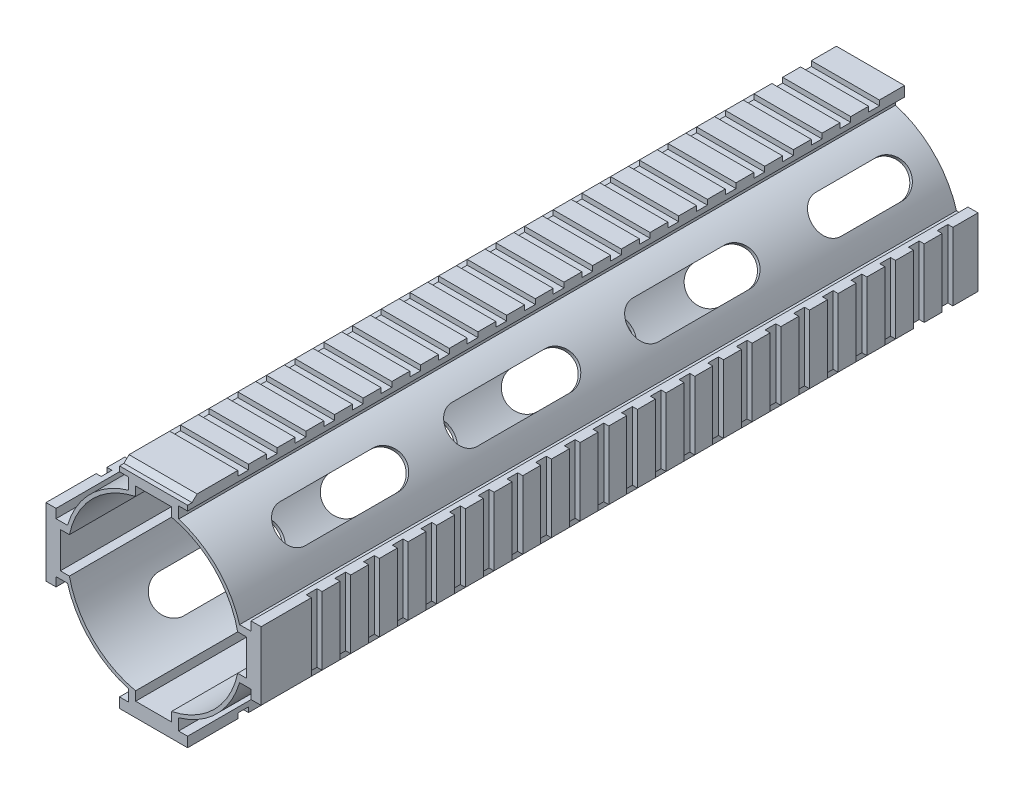
SolidWorks part; units mm, degrees
ref_plane "前视基准面" through (0, 0, 0) normal (0, 0, 1) x (1, 0, 0)
ref_plane "上视基准面" through (0, 0, 0) normal (0, 1, 0) x (1, 0, 0)
ref_plane "右视基准面" through (0, 0, 0) normal (1, 0, 0) x (0, 0, -1)
other "Configuration Table"
sketch "草图1" plane through (0, 0, 0) normal (0, 0, 1) x (1, 0, 0)
  line L1 (5, -23.4734) -> (5, -26)
  line L2 (5, -26) -> (-5, -26)
  line L3 (-5, -26) -> (-5, -23.4734)
  line L4 (0, 0) -> (0, -26) construction
  line L5 (-26, 5) -> (-23.4734, 5)
  line L6 (-26, -5) -> (-26, 5)
  line L7 (-23.4734, -5) -> (-26, -5)
  line L8 (5, 26) -> (5, 23.4734)
  line L9 (-5, 26) -> (5, 26)
  line L10 (-5, 23.4734) -> (-5, 26)
  line L11 (26, -5) -> (23.4734, -5)
  line L12 (26, 5) -> (26, -5)
  line L13 (23.4734, 5) -> (26, 5)
  arc A0 (5, -23.4734) -> (23.4734, -5) centre (0, 0) ccw
  arc A1 (-23.4734, -5) -> (-5, -23.4734) centre (0, 0) ccw
  arc A2 (-5, 23.4734) -> (-23.4734, 5) centre (0, 0) ccw
  arc A3 (23.4734, 5) -> (5, 23.4734) centre (0, 0) ccw
  point P22 (0, 0)
  dimension "D1" = 48
  dimension "D3" = 10
  dimension "D4" = 52
  dimension "D2" = 4
sketch "草图2" plane through (0, 0, 0) normal (0, 0, 1) x (1, 0, 0)
  line L1 (7, -24) -> (7, -27.2)
  line L3 (-7, -27.2) -> (-7, -24)
  line L4 (0, 0) -> (0, -28.1529) construction
  line L5 (-7, -27.2) -> (-9.5, -27.2)
  line L6 (-9.5, -27.2) -> (-9.5, -30)
  line L7 (-9.5, -30) -> (9.5, -30)
  line L8 (9.5, -30) -> (9.5, -27.2)
  line L9 (9.5, -27.2) -> (7, -27.2)
  line L10 (-24, -7) -> (-27.2, -7)
  line L11 (-27.2, 7) -> (-24, 7)
  line L12 (-27.2, 7) -> (-27.2, 9.5)
  line L13 (-27.2, 9.5) -> (-30, 9.5)
  line L14 (-30, 9.5) -> (-30, -9.5)
  line L15 (-30, -9.5) -> (-27.2, -9.5)
  line L16 (-27.2, -9.5) -> (-27.2, -7)
  line L17 (-5, 23.4734) -> (-5, 26) construction
  line L18 (-7, 24) -> (-7, 27.2)
  line L19 (7, 27.2) -> (7, 24)
  line L20 (7, 27.2) -> (9.5, 27.2)
  line L21 (9.5, 27.2) -> (9.5, 30)
  line L22 (9.5, 30) -> (-9.5, 30)
  line L23 (-9.5, 30) -> (-9.5, 27.2)
  line L24 (-9.5, 27.2) -> (-7, 27.2)
  line L25 (-5, 26) -> (5, 26) construction
  line L26 (24, 7) -> (27.2, 7)
  line L27 (27.2, -7) -> (24, -7)
  line L28 (27.2, -7) -> (27.2, -9.5)
  line L29 (27.2, -9.5) -> (30, -9.5)
  line L30 (30, -9.5) -> (30, 9.5)
  line L31 (30, 9.5) -> (27.2, 9.5)
  line L32 (27.2, 9.5) -> (27.2, 7)
  line L33 (5, 26) -> (5, 23.4734) construction
  line L34 (-25, 0) -> (-28.1529, 0) construction
  line L35 (0, 0) -> (0, 25) construction
  line L36 (25, 0) -> (28.1529, 0) construction
  line L37 (23.4734, 5) -> (26, 5) construction
  line L38 (26, 5) -> (26, -5) construction
  line L39 (26, -5) -> (23.4734, -5) construction
  line L40 (5, -23.4734) -> (5, -26) construction
  line L41 (5, -26) -> (-5, -26) construction
  line L42 (-5, -26) -> (-5, -23.4734) construction
  line L43 (-26, 5) -> (-23.4734, 5) construction
  line L44 (-23.4734, -5) -> (-26, -5) construction
  line L45 (-26, -5) -> (-26, 5) construction
  line L46 (-5, 23.4734) -> (-5, 26)
  line L47 (-5, 26) -> (5, 26)
  line L48 (5, 26) -> (5, 23.4734)
  line L49 (23.4734, 5) -> (26, 5)
  line L50 (26, 5) -> (26, -5)
  line L51 (26, -5) -> (23.4734, -5)
  line L52 (5, -23.4734) -> (5, -26)
  line L53 (5, -26) -> (-5, -26)
  line L54 (-5, -26) -> (-5, -23.4734)
  line L55 (-26, 5) -> (-23.4734, 5)
  line L56 (-23.4734, -5) -> (-26, -5)
  line L57 (-26, -5) -> (-26, 5)
  arc A0 (7, -24) -> (24, -7) centre (0, 0) ccw
  arc A1 (-24, -7) -> (-7, -24) centre (0, 0) ccw
  arc A2 (-7, 24) -> (-24, 7) centre (0, 0) ccw
  arc A3 (24, 7) -> (7, 24) centre (0, 0) ccw
  arc A4 (23.4734, 5) -> (5, 23.4734) centre (0, 0) ccw construction
  arc A5 (5, -23.4734) -> (23.4734, -5) centre (0, 0) ccw construction
  arc A6 (-23.4734, -5) -> (-5, -23.4734) centre (0, 0) ccw construction
  arc A7 (-5, 23.4734) -> (-23.4734, 5) centre (0, 0) ccw construction
  arc A8 (23.4734, 5) -> (5, 23.4734) centre (0, 0) ccw
  arc A9 (5, -23.4734) -> (23.4734, -5) centre (0, 0) ccw
  arc A10 (-23.4734, -5) -> (-5, -23.4734) centre (0, 0) ccw
  arc A11 (-5, 23.4734) -> (-23.4734, 5) centre (0, 0) ccw
  point P1 (0, -30)
  point P12 (7.5864, -29.0733)
  point P42 (0, 0)
  dimension "D1" = 50
  dimension "D3" = 14
  dimension "D4" = 19
  dimension "D5" = 60
  dimension "D6" = 2.8
  dimension "D7" = 2.8
  dimension "D2" = 4
extrude "凸台-拉伸2" add sketch "草图2" against normal blind 200
ref_plane "基准面2" through (14.2367, 14.2367, 0) normal (0.7071, 0.7071, 0) x (0.7071, -0.7071, 0)
sketch "草图5" plane through (14.2367, 14.2367, 0) normal (0.7071, 0.7071, 0) x (0.7071, -0.7071, 0)
  line L0 (0, 200) -> (0, 0) construction
  line L1 (12.0208, 200) -> (-12.0208, 200) construction
  line L2 (0, 188) -> (0, 171) construction
  line L3 (5, 188) -> (5, 171)
  line L4 (-5, 188) -> (-5, 171)
  line L5 (0, 145.5) -> (0, 120) construction
  line L6 (5, 145.5) -> (5, 120)
  line L7 (-5, 145.5) -> (-5, 120)
  line L8 (0, 95.5) -> (0, 69.5) construction
  line L9 (5, 95.5) -> (5, 69.5)
  line L10 (-5, 95.5) -> (-5, 69.5)
  line L11 (0, 47.5) -> (0, 21.5) construction
  line L12 (5, 47.5) -> (5, 21.5)
  line L13 (-5, 47.5) -> (-5, 21.5)
  arc A0 (5, 188) -> (-5, 188) centre (0, 188) ccw
  arc A1 (-5, 171) -> (5, 171) centre (0, 171) ccw
  arc A2 (5, 145.5) -> (-5, 145.5) centre (0, 145.5) ccw
  arc A3 (-5, 120) -> (5, 120) centre (0, 120) ccw
  arc A4 (5, 95.5) -> (-5, 95.5) centre (0, 95.5) ccw
  arc A5 (-5, 69.5) -> (5, 69.5) centre (0, 69.5) ccw
  arc A6 (5, 47.5) -> (-5, 47.5) centre (0, 47.5) ccw
  arc A7 (-5, 21.5) -> (5, 21.5) centre (0, 21.5) ccw
  point P7 (0, 179.5)
  point P12 (0, 132.75)
  point P19 (0, 82.5)
  point P26 (0, 34.5)
  point P33 (0, 0)
  point P35 (6.6279, 196.4967)
  dimension "D9" = 5
  dimension "D1" = 21.5
  dimension "D2" = 26
  dimension "D3" = 22
  dimension "D4" = 26
  dimension "D5" = 24.5
  dimension "D6" = 25.5
  dimension "D7" = 17
  dimension "D8" = 12
extrude "切除-拉伸2" cut sketch "草图5" along normal through all
sketch "草图6" plane through (0, 0, 0) normal (1, 0, 0) x (0, 0, -1)
  line L0 (200, 30) -> (0, 30) construction
  line L1 (190, 30) -> (193, 30)
  line L2 (190, 30) -> (190, 28.6)
  line L3 (190, 28.6) -> (193, 28.6)
  line L4 (193, 30) -> (193, 28.6)
  line L5 (200, 27.2) -> (200, 30) construction
  line L6 (185, 30) -> (185, 28.6)
  line L7 (182, 30) -> (185, 30)
  line L8 (182, 30) -> (182, 28.6)
  line L9 (182, 28.6) -> (185, 28.6)
  line L10 (177, 30) -> (177, 28.6)
  line L11 (174, 30) -> (177, 30)
  line L12 (174, 30) -> (174, 28.6)
  line L13 (174, 28.6) -> (177, 28.6)
  line L14 (169, 30) -> (169, 28.6)
  line L15 (166, 30) -> (169, 30)
  line L16 (166, 30) -> (166, 28.6)
  line L17 (166, 28.6) -> (169, 28.6)
  line L18 (161, 30) -> (161, 28.6)
  line L19 (158, 30) -> (161, 30)
  line L20 (158, 30) -> (158, 28.6)
  line L21 (158, 28.6) -> (161, 28.6)
  line L22 (153, 30) -> (153, 28.6)
  line L23 (150, 30) -> (153, 30)
  line L24 (150, 30) -> (150, 28.6)
  line L25 (150, 28.6) -> (153, 28.6)
  line L26 (145, 30) -> (145, 28.6)
  line L27 (142, 30) -> (145, 30)
  line L28 (142, 30) -> (142, 28.6)
  line L29 (142, 28.6) -> (145, 28.6)
  line L30 (137, 30) -> (137, 28.6)
  line L31 (134, 30) -> (137, 30)
  line L32 (134, 30) -> (134, 28.6)
  line L33 (134, 28.6) -> (137, 28.6)
  line L34 (129, 30) -> (129, 28.6)
  line L35 (126, 30) -> (129, 30)
  line L36 (126, 30) -> (126, 28.6)
  line L37 (126, 28.6) -> (129, 28.6)
  line L38 (121, 30) -> (121, 28.6)
  line L39 (118, 30) -> (121, 30)
  line L40 (118, 30) -> (118, 28.6)
  line L41 (118, 28.6) -> (121, 28.6)
  line L42 (113, 30) -> (113, 28.6)
  line L43 (110, 30) -> (113, 30)
  line L44 (110, 30) -> (110, 28.6)
  line L45 (110, 28.6) -> (113, 28.6)
  line L46 (105, 30) -> (105, 28.6)
  line L47 (102, 30) -> (105, 30)
  line L48 (102, 30) -> (102, 28.6)
  line L49 (102, 28.6) -> (105, 28.6)
  line L50 (97, 30) -> (97, 28.6)
  line L51 (94, 30) -> (97, 30)
  line L52 (94, 30) -> (94, 28.6)
  line L53 (94, 28.6) -> (97, 28.6)
  line L54 (89, 30) -> (89, 28.6)
  line L55 (86, 30) -> (89, 30)
  line L56 (86, 30) -> (86, 28.6)
  line L57 (86, 28.6) -> (89, 28.6)
  line L58 (81, 30) -> (81, 28.6)
  line L59 (78, 30) -> (81, 30)
  line L60 (78, 30) -> (78, 28.6)
  line L61 (78, 28.6) -> (81, 28.6)
  line L62 (73, 30) -> (73, 28.6)
  line L63 (70, 30) -> (73, 30)
  line L64 (70, 30) -> (70, 28.6)
  line L65 (70, 28.6) -> (73, 28.6)
  line L66 (65, 30) -> (65, 28.6)
  line L67 (62, 30) -> (65, 30)
  line L68 (62, 30) -> (62, 28.6)
  line L69 (62, 28.6) -> (65, 28.6)
  line L70 (57, 30) -> (57, 28.6)
  line L71 (54, 30) -> (57, 30)
  line L72 (54, 30) -> (54, 28.6)
  line L73 (54, 28.6) -> (57, 28.6)
  line L74 (49, 30) -> (49, 28.6)
  line L75 (46, 30) -> (49, 30)
  line L76 (46, 30) -> (46, 28.6)
  line L77 (46, 28.6) -> (49, 28.6)
  line L78 (41, 30) -> (41, 28.6)
  line L79 (38, 30) -> (41, 30)
  line L80 (38, 30) -> (38, 28.6)
  line L81 (38, 28.6) -> (41, 28.6)
  line L82 (33, 30) -> (33, 28.6)
  line L83 (30, 30) -> (33, 30)
  line L84 (30, 30) -> (30, 28.6)
  line L85 (30, 28.6) -> (33, 28.6)
  line L86 (25, 30) -> (25, 28.6)
  line L87 (22, 30) -> (25, 30)
  line L88 (22, 30) -> (22, 28.6)
  line L89 (22, 28.6) -> (25, 28.6)
  line L90 (17, 30) -> (17, 28.6)
  line L91 (14, 30) -> (17, 30)
  line L92 (14, 30) -> (14, 28.6)
  line L93 (14, 28.6) -> (17, 28.6)
  dimension "D1" = 3
  dimension "D2" = 7
  dimension "D3" = 1.4
  dimension "D5" = 8
  dimension "D4" = 23
extrude "切除-拉伸3" cut sketch "草图6" against normal mid plane 200
sketch "草图7" plane through (0, 0, 0) normal (1, 0, 0) x (0, 0, -1)
  line L0 (0, 28.6) -> (1.25, 28.6)
  line L1 (0, 27.2) -> (0, 30) construction
  line L2 (1.25, 28.6) -> (2.65, 30)
  line L3 (14, 30) -> (0, 30) construction
  line L4 (14, 28.6) -> (17, 28.6) construction
  line L5 (0, 24) -> (0, 27.2) construction
  line L6 (0, 28.6) -> (0, 30)
  line L7 (0, 30) -> (2.65, 30)
  dimension "D1" = 1.25
  dimension "D2" = 135
extrude "切除-拉伸4" cut sketch "草图7" against normal through all both and the other way through all
pattern_circular "阵列(圆周)1" count 4 over 360 about axis through (0, 0, 0) along (0, 0, 1) of "切除-拉伸2", "切除-拉伸3"
